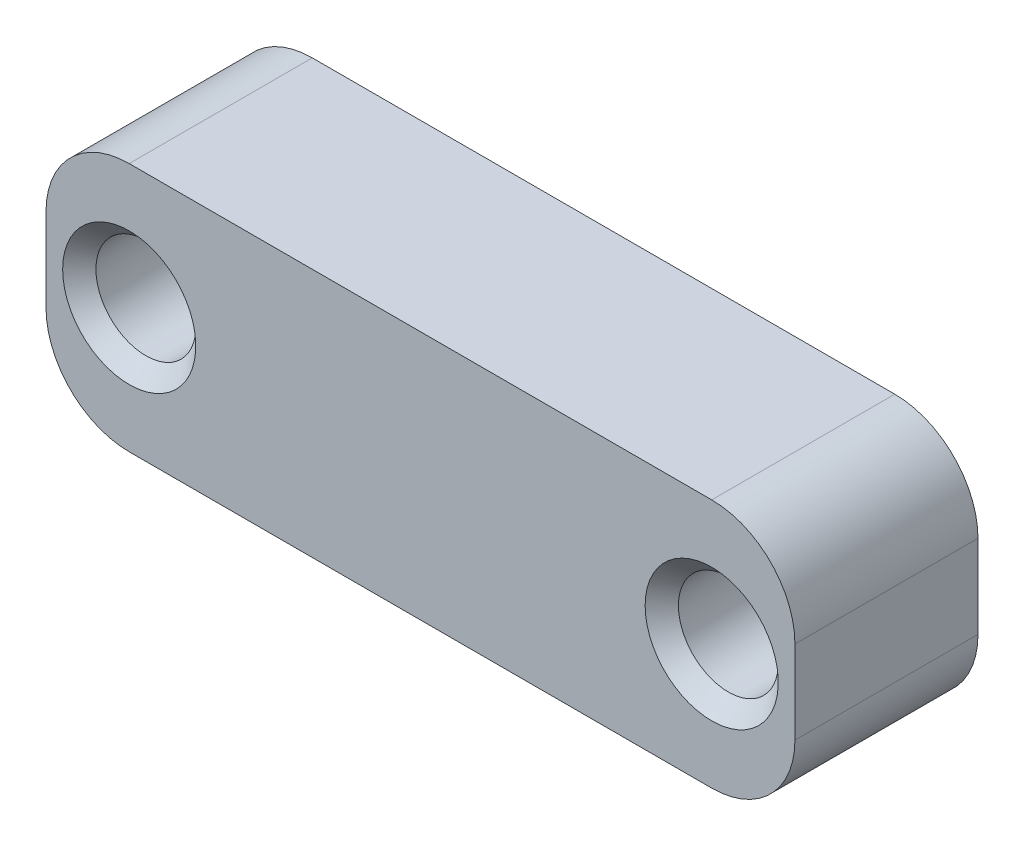
SolidWorks part; units mm, degrees
ref_plane "Alzado" through (0, 0, 0) normal (0, 0, 1) x (1, 0, 0)
ref_plane "Planta" through (0, 0, 0) normal (0, 1, 0) x (1, 0, 0)
ref_plane "Vista lateral" through (0, 0, 0) normal (1, 0, 0) x (0, 0, -1)
sketch "Croquis1" plane through (0, 0, 0) normal (0, 0, 1) x (1, 0, 0)
  line L0 (0, 0) -> (0, 15)
  line L1 (0, 15) -> (45, 15)
  line L2 (45, 15) -> (45, 0)
  line L3 (45, 0) -> (0, 0)
  circle A0 centre (5, 7.5) radius 3
  circle A1 centre (40, 7.5) radius 3
extrude "Saliente-Extruir1" add sketch "Croquis1" along normal blind 11
fillet "Redondeo1" radius 5 4 edges at (0, 0, 5.5) (45, 0, 5.5) (45, 15, 5.5) (0, 15, 5.5)
chamfer "Chaflán1" distance 1 angle 45 2 edges at (43, 7.5, 11) (8, 7.5, 11)
